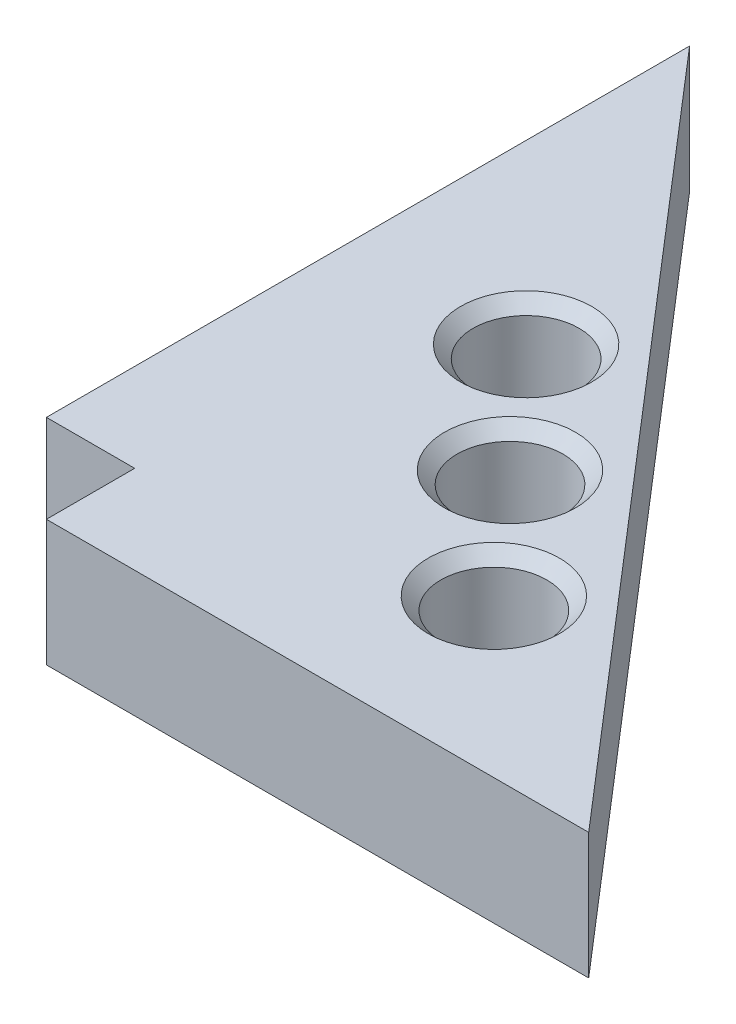
SolidWorks part; units mm, degrees
material "6061 Alloy"
ref_plane "Front Plane" through (0, 0, 0) normal (0, 0, 1) x (1, 0, 0)
ref_plane "Top Plane" through (0, 0, 0) normal (0, 1, 0) x (1, 0, 0)
ref_plane "Right Plane" through (0, 0, 0) normal (1, 0, 0) x (0, 0, -1)
sketch "Sketch1" plane through (0, 0, 0) normal (0, 1, 0) x (1, 0, 0)
  line L0 (0, 36.83) -> (0, 4.445)
  line L1 (0, 4.445) -> (4.445, 4.445)
  line L2 (4.445, 4.445) -> (4.445, 0)
  line L3 (4.445, 0) -> (31.75, 0)
  line L4 (31.75, 0) -> (0, 36.83)
  line L5 (0, 30.0223) -> (25.8813, 0) construction
  circle A0 centre (8.89, 19.7099) radius 2.667
  circle A1 centre (13.97, 13.8171) radius 2.667
  circle A2 centre (19.05, 7.9243) radius 2.667
  dimension "D6" = 5.334
  dimension "D1" = 4.445
  dimension "D2" = 4.445
  dimension "D3" = 36.83
  dimension "D4" = 31.75
  dimension "D5" = 4.445
  dimension "D7" = 19.05
  dimension "D8" = 13.97
  dimension "D9" = 8.89
extrude "Boss-Extrude1" add sketch "Sketch1" along normal mid plane 6.35
chamfer "Chamfer1" distance 0.635 angle 45 6 edges at (8.89, 3.175, -17.0429) (19.05, -3.175, -5.2573) (13.97, -3.175, -11.1501) (8.89, -3.175, -17.0429) (19.05, 3.175, -5.2573) (13.97, 3.175, -11.1501)
